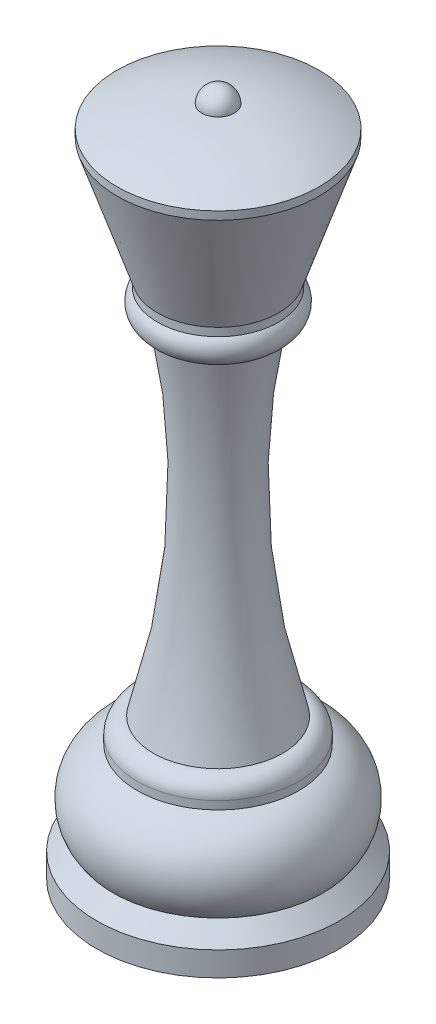
SolidWorks part; units mm, degrees
ref_plane "Front Plane" through (0, 0, 0) normal (0, 0, 1) x (1, 0, 0)
ref_plane "Top Plane" through (0, 0, 0) normal (0, 1, 0) x (1, 0, 0)
ref_plane "Right Plane" through (0, 0, 0) normal (1, 0, 0) x (0, 0, -1)
sketch "Sketch1" plane through (0, 0, 0) normal (0, 0, 1) x (1, 0, 0)
  line L0 (0, 0) -> (0, 134.9443) construction
  line L1 (0, 0) -> (-15, 0)
  line L2 (-15, 0) -> (-15, 3)
  line L3 (-15, 3) -> (-13, 5)
  line L4 (-10, 14.4541) -> (-10, 15.4541)
  line L5 (-7.5, 63.3651) -> (-7.5, 64.3651)
  line L6 (-7.5, 64.3651) -> (-12.5, 79.3651)
  line L7 (-12.5, 79.3651) -> (-12.5, 80.3651)
  line L8 (-2, 83) -> (0, 83)
  line L9 (0, 85) -> (0, 0)
  arc A0 (-13, 5) -> (-10, 14.4541) centre (-8.281, 8.7056) cw
  arc A1 (-10, 15.4541) -> (-8, 17.4541) centre (-8, 15.4541) cw
  arc A2 (-8, 17.4541) -> (-6, 59.8841) centre (-94.3611, 42.787) ccw
  arc A3 (-6, 59.8841) -> (-7.5, 63.3651) centre (-6.1633, 61.8774) cw
  arc A4 (-12.5, 80.3651) -> (-2, 83) centre (-1.3093, 58.0095) cw
  arc A5 (0, 85) -> (-2, 83) centre (0, 83) ccw
  point P12 (-14, 10.5203)
  point P16 (-8, 61.0859)
  dimension "D9" = 2
  dimension "D7" = 6
  dimension "D11" = 90
  dimension "D15" = 2
  dimension "D23" = 25
  dimension "D1" = 30
  dimension "D2" = 26
  dimension "D3" = 2
  dimension "D4" = 20
  dimension "D5" = 28
  dimension "D6" = 16
  dimension "D8" = 1
  dimension "D10" = 3
  dimension "D12" = 42.43
  dimension "D13" = 12
  dimension "D14" = 15
  dimension "D16" = 16
  dimension "D17" = 1
  dimension "D18" = 25
  dimension "D19" = 15
  dimension "D20" = 1
  dimension "D21" = 4
  dimension "D22" = 83
revolve "Revolve1" add sketch "Sketch1" angle 360 about L0
